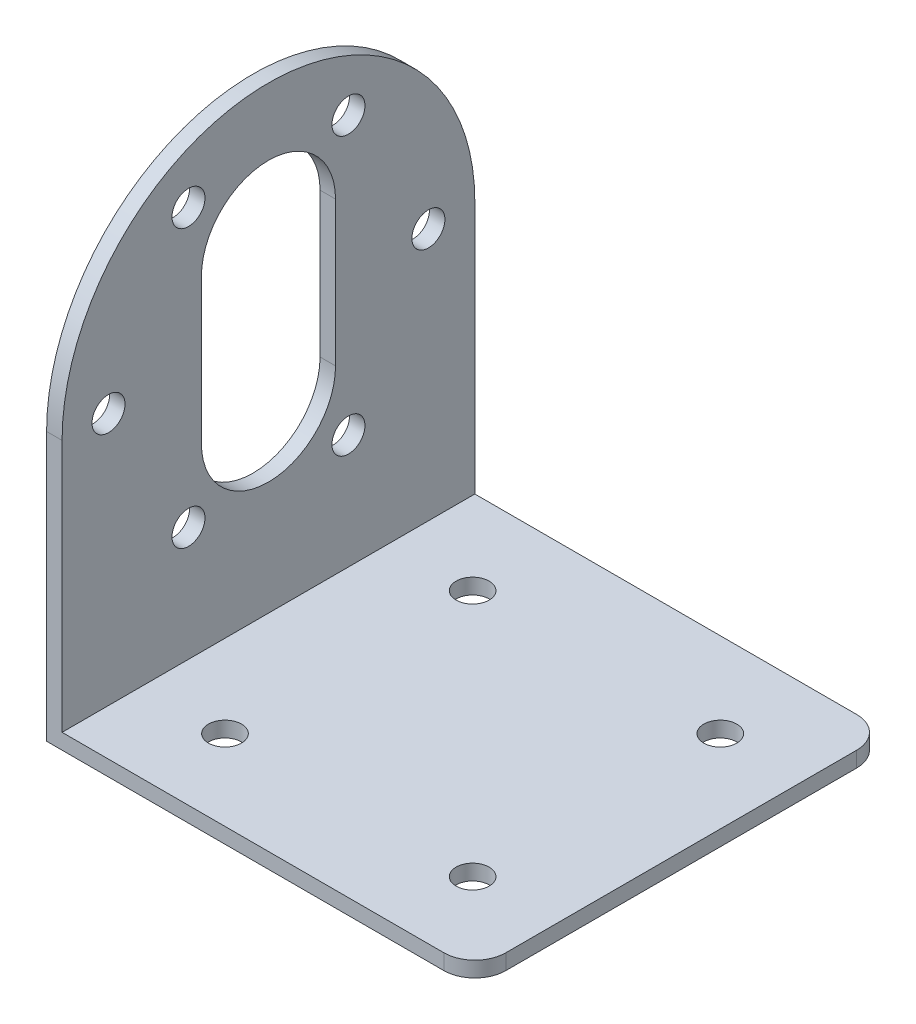
SolidWorks part; units mm, degrees
material "3003 合金"
ref_plane "前视基准面" through (0, 0, 0) normal (0, 0, 1) x (1, 0, 0)
ref_plane "上视基准面" through (0, 0, 0) normal (0, 1, 0) x (1, 0, 0)
ref_plane "右视基准面" through (0, 0, 0) normal (1, 0, 0) x (0, 0, -1)
sketch "草图1" plane through (0, 0, 0) normal (0, 1, 0) x (1, 0, 0)
  line L1 (0, 0) -> (41.5, 0)
  line L2 (0, 0) -> (0, 40)
  line L3 (0, 40) -> (41.5, 40)
  line L4 (41.5, 0) -> (41.5, 40)
  dimension "D1" = 41.5
  dimension "D2" = 40
extrude "凸台-拉伸1" add sketch "草图1" along normal blind 1.5
sketch "草图2" plane through (0, 1.5, 0) normal (0, 1, 0) x (1, 0, 0)
  line L0 (1.5, 40) -> (1.5, 0)
  line L1 (41.5, 40) -> (0, 40) construction
  line L2 (0, 0) -> (41.5, 0) construction
  line L3 (0, 40) -> (0, 0) construction
  line L4 (1.5, 40) -> (0, 40)
  line L5 (0, 40) -> (0, 0)
  line L6 (0, 0) -> (1.5, 0)
  dimension "D1" = 1.5
extrude "凸台-拉伸2" add sketch "草图2" along normal blind 44.5
sketch "草图3" plane through (0, 0, 0) normal (-1, 0, 0) x (0, 0, 1)
  line L0 (-20, 26) -> (-20, 0) construction
  line L2 (-40, 0) -> (0, 0) construction
  line L3 (-40, 23) -> (0, 23) construction
  line L4 (-40, 46) -> (-40, 0) construction
  line L5 (0, 46) -> (0, 0) construction
  line L6 (-40, 26) -> (-40, 46)
  line L7 (-40, 46) -> (0, 46)
  line L8 (0, 46) -> (0, 26)
  line L9 (-20, 26) -> (-20, 46) construction
  line L11 (-26.5, 19) -> (-26.5, 33)
  line L13 (-13.5, 19) -> (-13.5, 33)
  line L14 (-26.5, 19) -> (-13.5, 33) construction
  line L15 (-26.5, 33) -> (-13.5, 19) construction
  arc A0 (-40, 26) -> (0, 26) centre (-20, 26) cw
  arc A1 (-26.5, 33) -> (-13.5, 33) centre (-20, 33) cw
  arc A2 (-26.5, 19) -> (-13.5, 19) centre (-20, 19) ccw
  point P12 (-20, 26)
  point P25 (-20, 26)
  line M2 (0, 0) -> (0, 46)
  line M3 (0, 46) -> (-40, 46)
  line M4 (-40, 46) -> (-40, 0)
  dimension "D1" = 26
  dimension "D2" = 14
  dimension "D3" = 13
extrude "切除-拉伸1" cut sketch "草图3" against normal blind 1.5 contours A0 L7 M4 | A0 M3 M2 | L11 A2 L13 A1
sketch "草图4" plane through (0, 0, 0) normal (-1, 0, 0) x (0, 0, 1)
  line L0 (-20, 46) -> (-20, 0) construction
  line L1 (-40, 0) -> (0, 0) construction
  arc A0 (0, 26) -> (-40, 26) centre (-20, 26) ccw construction
  circle A1 centre (-20, 26) radius 15.5
  point P7 (-20, 26)
  dimension "D1" = 31
hole_wizard "Ø3.2 (3.2) 直径孔1" positions "草图6" profile "草图5" hole size "Ø3.2" standard "GB" end condition through all
sketch "草图6" plane through (0, 0, 0) normal (-1, 0, 0) x (0, 0, 1)
  line L12 (-20, 26) -> (0.7977, 26) construction
  line L14 (-20, 26) -> (-12.25, 39.4234) construction
  line L15 (-20, 46) -> (-20, 0) construction
  point P50 (-12.25, 39.4234)
  point P128 (-4.5, 26)
  point P129 (-12.25, 12.5766)
  point P130 (-27.75, 12.5766)
  point P131 (-35.5, 26)
  point P132 (-27.75, 39.4234)
  dimension "D1" = 6
  dimension "D3" = 30
  dimension "D2" = 15.5
sketch "草图5" plane through (0, 39.4234, -12.25) normal (0, 1, 0) x (0, 0, 1)
  line L0 (0, 0) -> (0, 41.5)
  line L1 (0, 41.5) -> (1.6, 41.5)
  line L2 (1.6, 41.5) -> (1.6, 0)
  line L5 (1.6, 0) -> (0, 0)
  line L11 (0, -6.35) -> (0, 107.95) construction
  dimension "通孔孔直径" = 3.2
  dimension "通孔孔深度" = 41.5
hole_wizard "Ø3.2 (3.2) 直径孔2" positions "草图9" profile "草图8" hole size "Ø3.2" standard "GB"
sketch "草图9" plane through (0, 0, 0) normal (0, -1, 0) x (-1, 0, 0)
  line L1 (-41.5, 0) -> (-41.5, 40) construction
  point P0 (-9.5, 31.786)
  point P2 (-33.5, 31.786)
  point P4 (-33.5, 7.786)
  point P6 (-9.5, 7.786)
  dimension "D1" = 24
  dimension "D2" = 24
  dimension "D3" = 8
sketch "草图8" plane through (9.5, 0, -31.786) normal (1, 0, 0) x (0, 0, -1)
  line L0 (0, 0) -> (0, 2.4614)
  line L1 (0, 2.4614) -> (1.6, 1.5)
  line L2 (1.6, 1.5) -> (1.6, 0)
  line L5 (1.6, 0) -> (0, 0)
  line L10 (0, 2.4614) -> (-1.6, 1.5) construction
  line L11 (0, -6.35) -> (0, 107.95) construction
  dimension "孔直径" = 3.2
  dimension "孔深度" = 1.5
  dimension "导头角度" = 118
fillet "圆角1" radius 3 2 edges at (41.5, 0.75, -40) (41.5, 0.75, 0)
